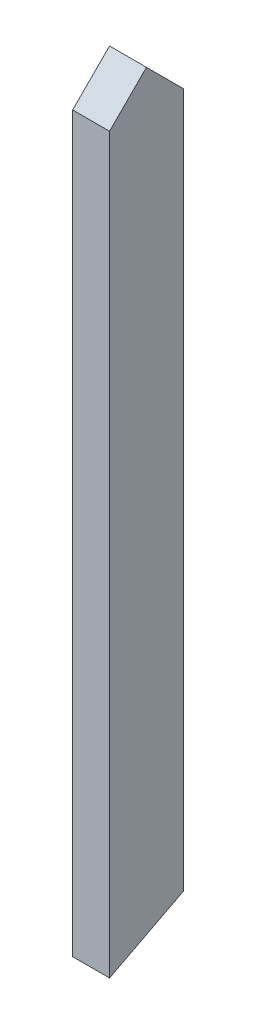
SolidWorks part; units mm, degrees
ref_plane "Спереди" through (0, 0, 0) normal (0, 0, 1) x (1, 0, 0)
ref_plane "Сверху" through (0, 0, 0) normal (0, 1, 0) x (1, 0, 0)
ref_plane "Справа" through (0, 0, 0) normal (1, 0, 0) x (0, 0, -1)
other "Configuration Table"
sketch "Эскиз1" plane through (0, 0, 0) normal (0, 1, 0) x (1, 0, 0)
  line L1 (12.5, 25) -> (-12.5, 25)
  line L2 (12.5, 25) -> (12.5, -25)
  line L3 (12.5, -25) -> (-12.5, -25)
  line L4 (-12.5, 25) -> (-12.5, -25)
  line L5 (12.5, 25) -> (-12.5, -25) construction
  line L6 (12.5, -25) -> (-12.5, 25) construction
  point P0 (0, 0)
extrude "Бобышка-Вытянуть1" add sketch "Эскиз1" along normal blind 521.512
sketch "Эскиз2" plane through (12.5, 0, 0) normal (1, 0, 0) x (0, 0, -1)
  line L0 (-25, 521.512) -> (0, 521.512)
  line L2 (25, 521.512) -> (25, 0) construction
  line L3 (-25, 521.512) -> (-25, 496.512)
  line L4 (-25, 521.512) -> (-25, 0) construction
  line L5 (-25, 496.512) -> (0, 521.512)
  line L7 (25, 0) -> (25, 25.9036)
  line L8 (25, 25.9036) -> (-25, 0)
  line L9 (-25, 0) -> (25, 0)
extrude "Вырез-Вытянуть1" cut sketch "Эскиз2" against normal blind 521.51
sketch "Эскиз3" plane through (12.5, 0, 0) normal (1, 0, 0) x (0, 0, -1)
  line L0 (0, 521.512) -> (25, 496.512)
  line L1 (25, 521.512) -> (25, 25.9036) construction
  line L2 (25, 496.512) -> (25, 521.512)
  line L3 (25, 521.512) -> (0, 521.512)
extrude "Вырез-Вытянуть2" cut sketch "Эскиз3" against normal blind 521.51
